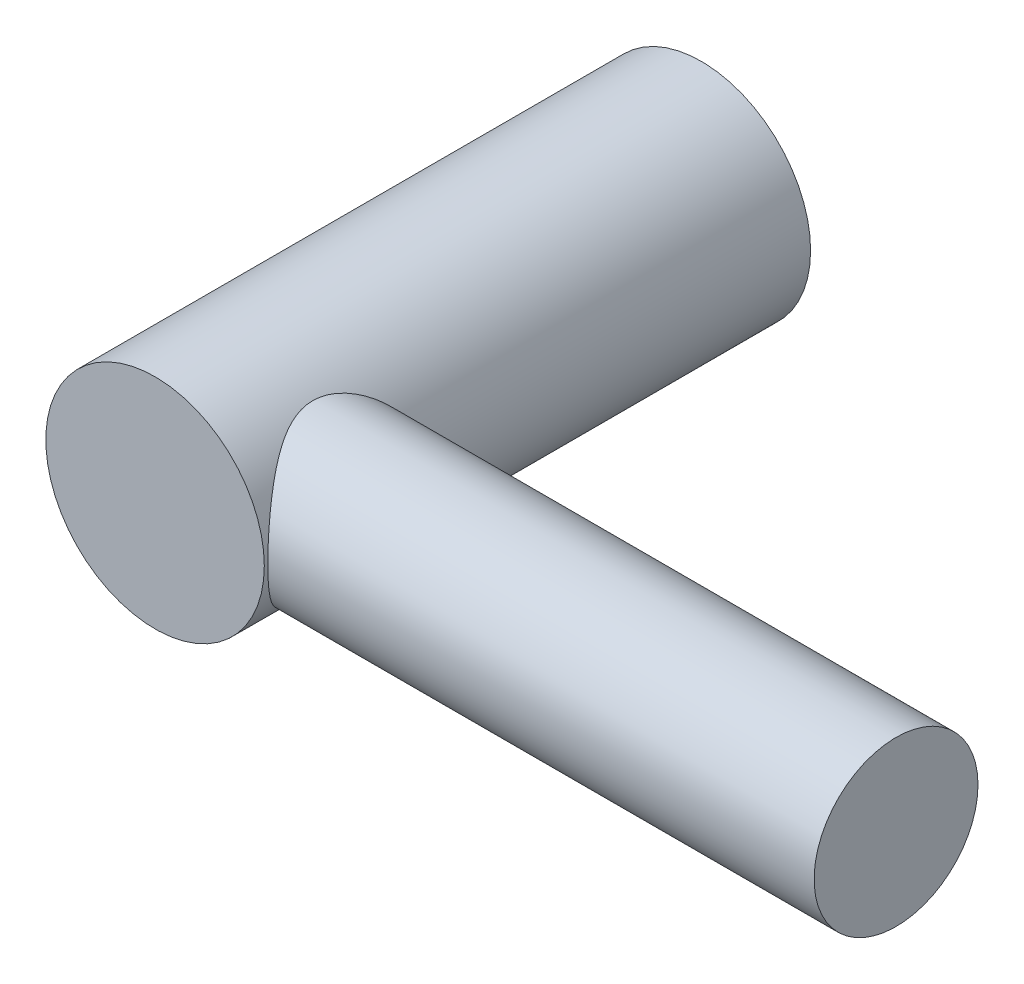
SolidWorks part; units mm, degrees
ref_plane "Front Plane" through (0, 0, 0) normal (0, 0, 1) x (1, 0, 0)
ref_plane "Top Plane" through (0, 0, 0) normal (0, 1, 0) x (1, 0, 0)
ref_plane "Right Plane" through (0, 0, 0) normal (1, 0, 0) x (0, 0, -1)
sketch "Sketch1" plane through (0, 0, 0) normal (0, 0, 1) x (1, 0, 0)
  circle A0 centre (0, 0) radius 25.4
extrude "Boss-Extrude1" add sketch "Sketch1" along normal blind 127
sketch "Sketch2" plane through (0, 0, 0) normal (1, 0, 0) x (0, 0, -1)
  circle A0 centre (-107.1309, 0) radius 19.05
  dimension "D1" = 38.1
extrude "Boss-Extrude2" add sketch "Sketch2" along normal blind 152.4
